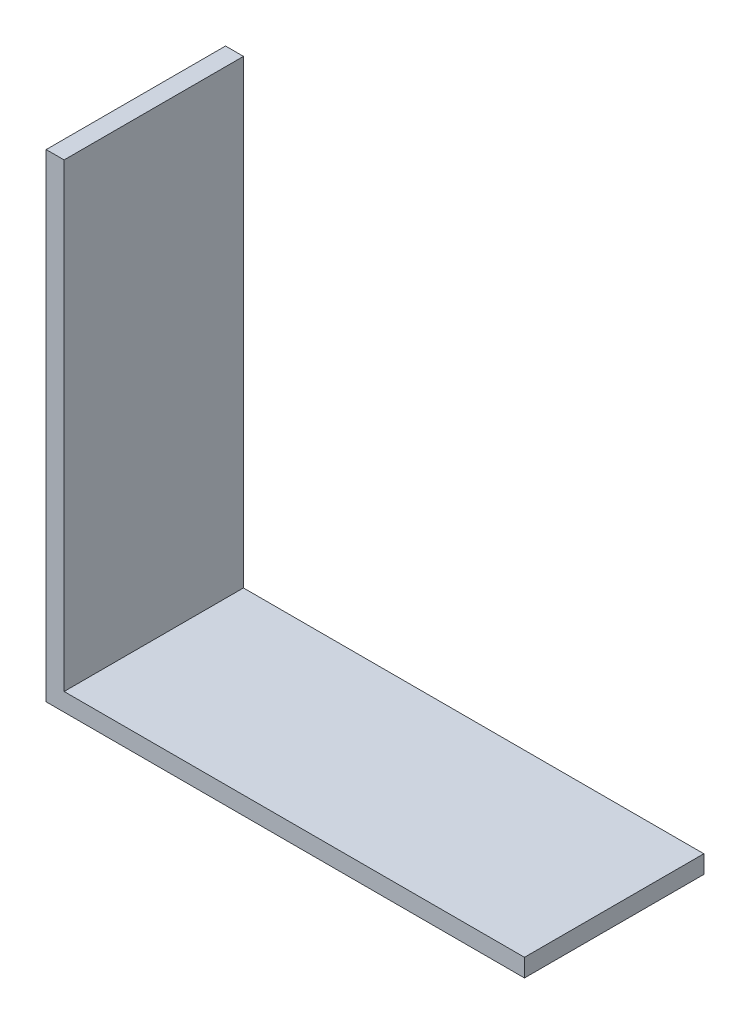
SolidWorks part; units mm, degrees
material "Листовая углеродистая сталь 1023 (SS)"
ref_plane "Спереди" through (0, 0, 0) normal (0, 0, 1) x (1, 0, 0)
ref_plane "Сверху" through (0, 0, 0) normal (0, 1, 0) x (1, 0, 0)
ref_plane "Справа" through (0, 0, 0) normal (1, 0, 0) x (0, 0, -1)
sketch "Эскиз1" plane through (0, 0, 0) normal (0, 0, 1) x (1, 0, 0)
  line L0 (0, 0) -> (40, 0)
  line L1 (40, 0) -> (40, 1.5)
  line L2 (40, 1.5) -> (1.5, 1.5)
  line L3 (1.5, 1.5) -> (1.5, 40)
  line L4 (1.5, 40) -> (0, 40)
  line L5 (0, 40) -> (0, 0)
  dimension "D1" = 1.5
  dimension "D2" = 1.5
  dimension "D3" = 40
  dimension "D4" = 40
extrude "Бобышка-Вытянуть1" add sketch "Эскиз1" along normal blind 15
